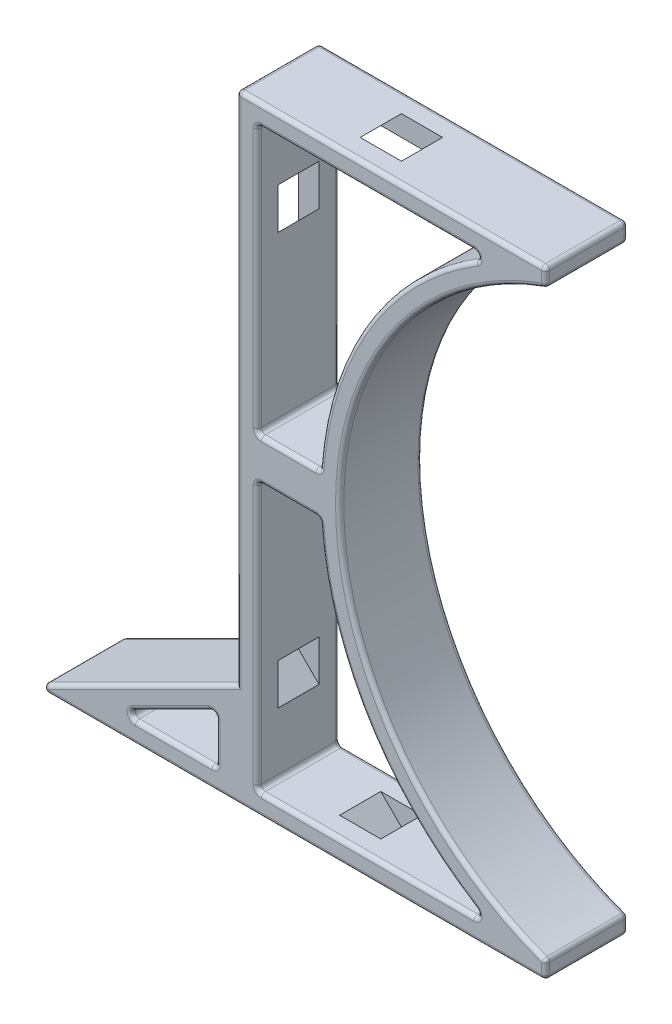
SolidWorks part; units mm, degrees
ref_plane "Front Plane" through (0, 0, 0) normal (0, 0, 1) x (1, 0, 0)
ref_plane "Top Plane" through (0, 0, 0) normal (0, 1, 0) x (1, 0, 0)
ref_plane "Right Plane" through (0, 0, 0) normal (1, 0, 0) x (0, 0, -1)
sketch "Sketch1" plane through (0, 0, 0) normal (0, 0, 1) x (1, 0, 0)
  line L0 (0, 0) -> (50000, 0) construction
  line L1 (-6.35, -6.3933) -> (-6.35, 49993.6067) construction
  line L2 (-6.35, 19.05) -> (-25.4, 19.05)
  line L3 (-25.4, 19.05) -> (-25.4, 0)
  line L4 (-25.4, 0) -> (-19.05, 0)
  line L5 (-6.35, 19.05) -> (-6.35, 17.9605)
  line L6 (-24.13, 17.78) -> (-24.13, 1.27)
  line L7 (-24.13, 1.27) -> (-20.2803, 1.27)
  line L8 (-9.8374, 17.78) -> (-9.8374, 17.78)
  line L9 (-9.8374, 17.78) -> (-24.13, 17.78)
  circle A0 centre (0, 0) radius 19.05 construction
  arc A1 (-19.05, 0) -> (-6.35, 17.9605) centre (0, 0) cw
  arc A2 (-20.2803, 1.27) -> (-9.8374, 17.78) centre (0, 0) cw
  dimension "D1" = 38.1
  dimension "D2" = 6.35
  dimension "D4" = 19.05
  dimension "D5" = 19.05
  dimension "D3" = 1.27
extrude "Boss-Extrude1" add sketch "Sketch1" against normal blind 2.54
mirror "Mirror1" about plane through (0, 0, 0) normal (0, 1, 0) of "Boss-Extrude1"
sketch "Sketch2" plane through (0, 0, -2.54) normal (0, 0, -1) x (-1, 0, 0)
  line L0 (0, 0) -> (-50000, 0) construction
  line L1 (25.4, 10.16) -> (16.51, 19.05)
  line L2 (25.4, 19.05) -> (25.4, -19.05) construction
  line L3 (6.35, 19.05) -> (25.4, 19.05) construction
  line L4 (16.51, 19.05) -> (19.05, 19.05)
  line L5 (19.05, 19.05) -> (25.4, 12.7)
  line L6 (25.4, 12.7) -> (25.4, 10.16)
  dimension "D1" = 2.54
  dimension "D2" = 6.35
  dimension "D3" = 6.35
extrude "Cut-Extrude2" cut sketch "Sketch2" against normal blind 1.27
mirror "Mirror2" about plane through (0, 0, 0) normal (0, 1, 0) of "Cut-Extrude2"
mirror "Mirror3" about plane through (0, 0, -2.54) normal (0, 0, -1) of "Mirror2", "Cut-Extrude2", "Boss-Extrude1", "Mirror1"
sketch "Sketch4" plane through (0, 0, -5.08) normal (0, 0, -1) x (-1, 0, 0)
  line L0 (25.4, -19.05) -> (38.1, -19.05)
  line L1 (38.1, -19.05) -> (25.4, -12.7)
  line L2 (25.4, 19.05) -> (25.4, -19.05) construction
  line L3 (25.4, -12.7) -> (25.4, -19.05)
  line L4 (26.67, -17.78) -> (32.7202, -17.78)
  line L5 (32.7202, -17.78) -> (26.67, -14.7549)
  line L6 (26.67, -14.7549) -> (26.67, -17.78)
  dimension "D1" = 6.35
  dimension "D2" = 12.7
  dimension "D3" = 1.27
extrude "Boss-Extrude2" add sketch "Sketch4" against normal up to surface (5.08 mm away)
fillet "Fillet1" radius 0.254 17 edges at (-25.4, 19.05, -2.54) (-6.35, 17.9605, -2.54) (-6.35, 19.05, -2.54) (-6.35, -19.05, -2.54) (-6.35, -17.9605, -2.54) (-9.8374, 17.78, -2.54) (-24.13, 17.78, -2.54) (-20.2803, 1.27, -2.54) (-24.13, 1.27, -2.54) (-20.2803, -1.27, -2.54) (-24.13, -1.27, -2.54) (-9.8374, -17.78, -2.54) (-24.13, -17.78, -2.54) (-26.67, -14.7549, -2.54) (-26.67, -17.78, -2.54) (-32.7202, -17.78, -2.54) (-38.1, -19.05, -2.54)
fillet "Fillet2" radius 0.254 70 edges at (-26.7444, -17.7056, 0) (-26.67, -16.3459, 0) (-26.67, -16.3459, -5.08) (-26.7905, -14.9498, 0) (-29.3977, -16.1188, -5.08) (-29.3977, -16.1188, 0) (-31.8914, -17.5844, 0) (-29.2841, -17.78, 0) (-29.2841, -17.78, -5.08) (-20.3447, -1.3379, 0) (-22.1967, -1.27, -5.08) (-22.1967, -1.27, 0) (-24.0556, -1.3444, 0) (-24.13, -9.525, -5.08) (-24.13, -9.525, 0) (-24.0556, -17.7056, 0) (-17.3262, -17.78, 0) (-17.3262, -17.78, -5.08) (-10.5319, -17.5951, 0) (-17.3569, -10.566, 0) (-17.3569, -10.566, -5.08) (-6.4244, 18.9756, 0) (-6.35, 18.4676, 0) (-6.3959, 17.9935, 0) (-19.05, 0, 0) (-6.3959, -17.9935, 0) (-6.35, -18.4676, 0) (-6.35, -18.4676, -5.08) (-6.4244, -18.9756, 0) (-21.814, -19.05, -5.08) (-21.814, -19.05, 0) (-37.2712, -18.8544, 0) (-31.2688, -15.6344, -5.08) (-31.2688, -15.6344, 0) (-25.4, 3.048, 0) (-25.3256, 18.9756, 0) (-15.875, 19.05, 0) (-24.0556, 1.3444, 0) (-22.1967, 1.27, 0) (-20.3447, 1.3379, 0) (-17.3569, 10.566, 0) (-10.5319, 17.5951, 0) (-17.3262, 17.78, 0) (-24.0556, 17.7056, 0) (-24.13, 9.525, 0) (-26.7444, -17.7056, -5.08) (-31.8914, -17.5844, -5.08) (-26.7905, -14.9498, -5.08) (-24.0556, -1.3444, -5.08) (-20.3447, -1.3379, -5.08) (-10.5319, -17.5951, -5.08) (-24.0556, -17.7056, -5.08) (-20.3447, 1.3379, -5.08) (-22.1967, 1.27, -5.08) (-24.0556, 1.3444, -5.08) (-24.13, 9.525, -5.08) (-24.0556, 17.7056, -5.08) (-17.3262, 17.78, -5.08) (-10.5319, 17.5951, -5.08) (-17.3569, 10.566, -5.08) (-37.2712, -18.8544, -5.08) (-6.4244, -18.9756, -5.08) (-6.3959, -17.9935, -5.08) (-19.05, 0, -5.08) (-6.3959, 17.9935, -5.08) (-6.35, 18.4676, -5.08) (-6.4244, 18.9756, -5.08) (-15.875, 19.05, -5.08) (-25.3256, 18.9756, -5.08) (-25.4, 3.048, -5.08)
